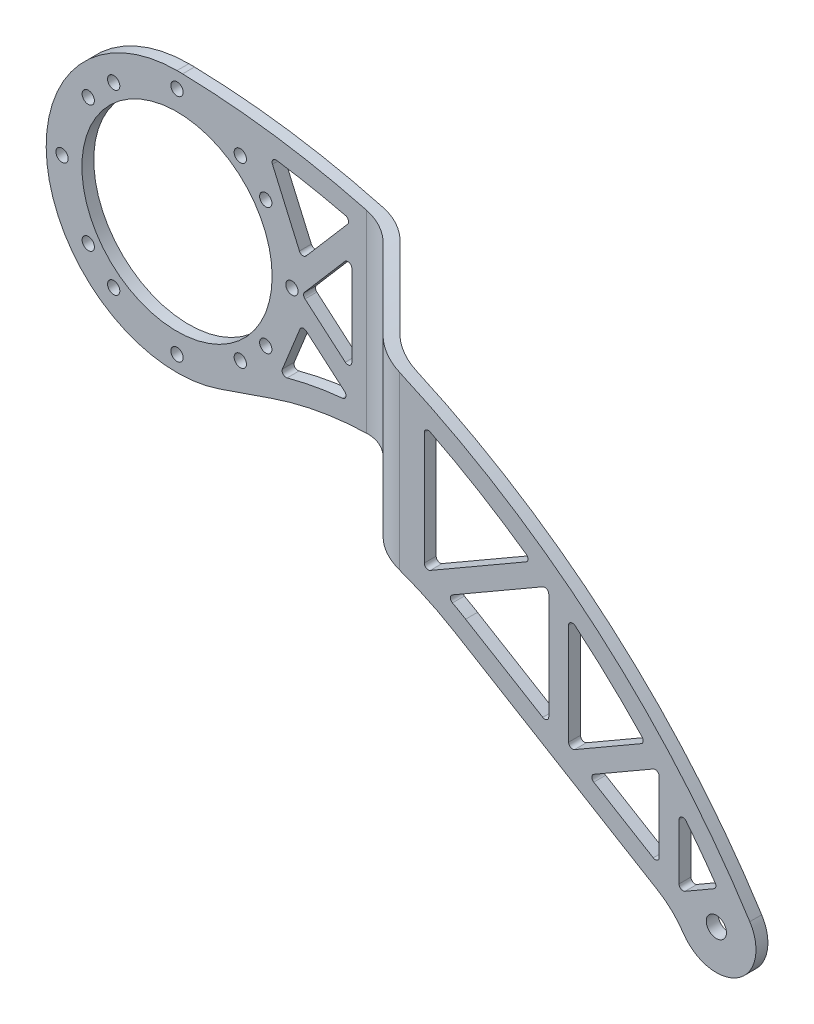
SolidWorks part; units mm, degrees
material "6061 合金"
ref_plane "前视基准面" through (0, 0, 0) normal (0, 0, 1) x (1, 0, 0)
ref_plane "上视基准面" through (0, 0, 0) normal (0, 1, 0) x (1, 0, 0)
ref_plane "右视基准面" through (0, 0, 0) normal (1, 0, 0) x (0, 0, -1)
other "Configuration Table"
sketch "草图1" plane through (0, 0, 0) normal (0, 0, 1) x (1, 0, 0)
  line L0 (-38.6665, 0) -> (31.2744, 0) construction
  line L1 (0, 22.4607) -> (0, -30.1372) construction
  line L4 (10.7304, -31.2067) -> (23.987, -26.6485)
  line L5 (91.2325, -33.7454) -> (142.3676, -64.5004)
  line L6 (157.0595, -65.0562) -> (0, 0) construction
  circle A7 centre (157.0595, -65.0562) radius 2.55
  arc A9 (0, 33) -> (10.7304, -31.2067) centre (0, 0) ccw
  arc A10 (148.7262, -70.5839) -> (165.4995, -59.6928) centre (157.0595, -65.0562) ccw
  arc A11 (1.4146, 32.9833) -> (165.4995, -59.6928) centre (-3.3007, -166.9611) cw
  arc A12 (23.987, -26.6485) -> (91.2325, -33.7454) centre (50, -102.3011) cw
  arc A13 (142.3676, -64.5004) -> (148.7262, -70.5839) centre (132.0595, -81.6393) cw
  arc A14 (1.4146, 32.9833) -> (0, 33) centre (0, -27) ccw
  dimension "D1" = 60
  dimension "D2" = 5.1
  dimension "D3" = 22.5
  dimension "D4" = 33
  dimension "D6" = 80
  dimension "D7" = 20
  dimension "D8" = 10
  dimension "D10" = 200
  dimension "D11" = 50
  dimension "D5" = 130
  dimension "D9" = 170
  dimension "D12" = 25
extrude "凸台-拉伸1" add sketch "草图1" along normal blind 3 and the other way blind 21
sketch "草图6" plane through (0, 0, 0) normal (0, 1, 0) x (1, 0, 0)
  line L0 (-33, 0) -> (47.8579, 0)
  line L2 (54.9289, 2.9289) -> (73, 21)
  line L3 (10.7304, 21) -> (-33, 21) construction
  line L5 (53.2426, -3) -> (71.3137, 15.0711)
  line L7 (78.3848, 18) -> (167.0595, 18)
  line L8 (167.0595, 18) -> (167.0595, -3)
  line L9 (167.0595, -3) -> (53.2426, -3)
  line L10 (73, 21) -> (-33, 21)
  line L12 (-33, 21) -> (-33, 0)
  line L13 (-33, 21) -> (-33, -3) construction
  line L14 (167.0595, -3) -> (167.0595, 21) construction
  line L15 (165.4995, 21) -> (1.4146, 21) construction
  line L16 (1.4146, -3) -> (165.4995, -3) construction
  arc A0 (71.3137, 15.0711) -> (78.3848, 18) centre (78.3848, 8) cw
  arc A1 (47.8579, 0) -> (54.9289, 2.9289) centre (47.8579, 10) ccw
  point P25 (52, 0)
  dimension "D5" = 10
  dimension "D1" = 3
  dimension "D2" = 3
  dimension "D3" = 45
  dimension "D4" = 85
extrude "切除-拉伸3" cut sketch "草图6" against normal through all both and the other way through all
sketch "草图2" plane through (0, 0, 3) normal (0, 0, 1) x (1, 0, 0)
  circle A0 centre (-29, 0) radius 1.55
  circle A2 centre (0, 0) radius 29 construction
  circle A3 centre (0, -29) radius 1.55
  circle A4 centre (0, 29) radius 1.55
  circle A5 centre (29, 0) radius 1.55
  dimension "D2" = 3.1
  dimension "D1" = 29
extrude "切除-拉伸1" cut sketch "草图2" against normal through all
sketch "草图4" plane through (0, 0, 3) normal (0, 0, 1) x (1, 0, 0)
  line L0 (35.2189, 0) -> (0, 0) construction
  line L1 (0, 0) -> (0, 39.685) construction
  line L2 (22.3882, 15.9693) -> (0, 0) construction
  line L3 (0, 0) -> (15.9693, 22.3882) construction
  line L4 (15.9693, -22.3882) -> (0, 0) construction
  line L5 (0, 0) -> (22.3882, -15.9693) construction
  line L6 (-22.3882, -15.9693) -> (0, 0) construction
  line L7 (0, 0) -> (-15.9693, -22.3882) construction
  line L8 (-15.9693, 22.3882) -> (0, 0) construction
  line L9 (0, 0) -> (-22.3882, 15.9693) construction
  circle A0 centre (0, 0) radius 27.5 construction
  circle A1 centre (-22.3882, 15.9693) radius 1.55
  circle A2 centre (15.9693, 22.3882) radius 1.55
  circle A3 centre (-15.9693, -22.3882) radius 1.55
  circle A4 centre (22.3882, -15.9693) radius 1.55
  circle A5 centre (-15.9693, 22.3882) radius 1.55
  circle A6 centre (22.3882, 15.9693) radius 1.55
  circle A7 centre (15.9693, -22.3882) radius 1.55
  circle A8 centre (-22.3882, -15.9693) radius 1.55
  point P16 (0, 0)
  dimension "D1" = 55
  dimension "D5" = 3.1
  dimension "D2" = 35.5
  dimension "D3" = 19
  dimension "D4" = 4
extrude "切除-拉伸2" cut sketch "草图4" against normal through all
fillet "圆角2" radius 10 2 edges at (73, -3.8831, -21) (53.2426, 1.2564, 3)
sketch "草图9" plane through (0, 0, -21) normal (0, 0, -1) x (-1, 0, 0)
  circle A0 centre (-157.0595, -65.0562) radius 7.75
  dimension "D1" = 15.5
sketch "草图10" plane through (0, 0, 3) normal (0, 0, 1) x (1, 0, 0)
  circle A0 centre (0, 0) radius 24
  dimension "D1" = 48
extrude "切除-拉伸5" cut sketch "草图10" against normal through all
sketch "草图12" plane through (0, 0, -18) normal (0, 0, 1) x (1, 0, 0)
  line L0 (83.3848, 6.0917) -> (83.3848, -22.3996)
  line L1 (84.8848, -23.2657) -> (109.0475, -9.3153)
  line L4 (93.8095, -29.4607) -> (144.9447, -60.2157)
  line L5 (83.3848, 7.7118) -> (83.3848, -24.1317)
  line L11 (113.2813, -12.6445) -> (90.4641, -25.818)
  line L12 (93.8095, -29.4607) -> (113.2659, -41.1626)
  line L13 (114.7813, -13.5105) -> (114.7813, -40.3057)
  line L14 (119.7813, -17.8314) -> (119.7813, -43.3492)
  line L15 (121.2813, -44.2152) -> (138.1188, -34.4941)
  line L16 (126.1486, -47.1786) -> (141.1555, -38.5143)
  line L17 (142.6555, -39.3804) -> (142.6555, -57.0705)
  line L18 (147.6555, -46.3571) -> (147.6555, -60.3684)
  line L19 (126.1332, -48.9016) -> (141.1401, -57.9274)
  line L20 (156.4448, -57.026) -> (149.1555, -61.2345)
  arc A0 (109.124, -7.6322) -> (84.8368, 6.9837) centre (-3.3007, -166.9611) ccw
  arc A1 (138.3452, -32.9408) -> (121.4209, -17.0627) centre (-3.3007, -166.9611) ccw
  arc A2 (161.2795, -62.3745) -> (83.3848, 7.7118) centre (-3.3007, -166.9611) ccw
  arc A4 (156.7656, -55.5888) -> (149.4388, -45.7354) centre (-3.3007, -166.9611) ccw
  arc A5 (149.4263, -63.6561) -> (144.9447, -60.2157) centre (132.0595, -81.6393) ccw construction
  arc A22 (152.8929, -67.82) -> (144.9447, -60.2157) centre (132.0595, -81.6393) ccw
  arc A24 (152.8929, -67.82) -> (161.2795, -62.3745) centre (157.0595, -65.0562) ccw
  arc A25 (147.6555, -46.3571) -> (149.4388, -45.7354) centre (148.6555, -46.3571) cw
  arc A26 (126.1486, -47.1786) -> (126.1332, -48.9016) centre (126.6486, -48.0446) ccw
  arc A27 (141.1555, -38.5143) -> (142.6555, -39.3804) centre (141.6555, -39.3804) cw
  arc A28 (138.1188, -34.4941) -> (138.3452, -32.9408) centre (137.6188, -33.628) ccw
  arc A29 (119.7813, -43.3492) -> (121.2813, -44.2152) centre (120.7813, -43.3492) ccw
  arc A30 (119.7813, -17.8314) -> (121.4209, -17.0627) centre (120.7813, -17.8314) cw
  arc A31 (114.7813, -40.3057) -> (113.2659, -41.1626) centre (113.7813, -40.3057) cw
  arc A32 (90.4641, -25.818) -> (90.4877, -27.5633) centre (90.9641, -26.684) ccw
  arc A33 (113.2813, -12.6445) -> (114.7813, -13.5105) centre (113.7813, -13.5105) cw
  arc A34 (109.0475, -9.3153) -> (109.124, -7.6322) centre (108.5475, -8.4493) ccw
  arc A35 (84.8848, -23.2657) -> (83.3848, -22.3996) centre (84.3848, -22.3996) cw
  arc A36 (84.8368, 6.9837) -> (83.3848, 6.0917) centre (84.3848, 6.0917) ccw
  arc A37 (142.6555, -57.0705) -> (141.1401, -57.9274) centre (141.6555, -57.0705) cw
  arc A38 (147.6555, -60.3684) -> (149.1555, -61.2345) centre (148.6555, -60.3684) ccw
  arc A39 (156.7656, -55.5888) -> (156.4448, -57.026) centre (155.9448, -56.16) cw
  arc A41 (93.8095, -29.4607) -> (83.3848, -24.1317) centre (50, -102.3011) ccw
  arc A42 (93.8095, -29.4607) -> (90.4877, -27.5633) centre (50, -102.3011) ccw
  point P5 (147.6555, -62.1005)
  point P19 (83.3848, -24.1317)
  point P30 (147.6555, -62.1005)
  point P35 (124.6791, -48.027)
  point P38 (142.6555, -37.6483)
  point P41 (139.212, -33.8629)
  point P44 (399.0304, 162.0422)
  point P45 (119.7813, -45.0813)
  point P54 (114.7813, -11.7784)
  point P57 (110.3955, -8.537)
  dimension "D6" = 60
  dimension "D9" = 5
  dimension "D2" = 5
  dimension "D11" = 60
  dimension "D12" = 1
  dimension "D13" = 1
  dimension "D7" = 1
  dimension "D3" = 5
  dimension "D4" = 60
  dimension "D5" = 60
  dimension "D8" = 5
  dimension "D1" = 5
extrude "切除-拉伸6" cut sketch "草图12" against normal through all
sketch "草图13" plane through (0, 0, 3) normal (0, 0, 1) x (1, 0, 0)
  line L0 (32.9388, 0) -> (0, 0) construction
  line L2 (24.0827, 24.5625) -> (30.8907, 9.0204)
  line L3 (32.565, 8.7697) -> (43.0399, 20.9561)
  line L4 (44.1005, -17.5061) -> (44.1005, 22.19)
  line L5 (9.1045, -26.4784) -> (22.3612, -21.9202)
  line L6 (44.1005, -8.7346) -> (44.1005, 11.822)
  line L8 (32.1804, 0.6518) -> (42.3422, 12.4738)
  line L9 (32.2869, -0.7584) -> (42.4487, -9.493)
  line L10 (32.5853, -7.6081) -> (42.2904, -15.9502)
  line L11 (31.0063, -7.9916) -> (26.5896, -18.9173)
  circle A0 centre (22.3882, -15.9693) radius 1.55 construction
  arc A1 (41.7358, -17.7038) -> (42.2904, -15.9502) centre (41.6386, -16.7085) ccw
  arc A2 (26.5896, -18.9173) -> (27.7781, -20.2573) centre (27.5167, -19.2921) ccw
  arc A3 (32.1804, 0.6518) -> (32.2869, -0.7584) centre (32.9388, 0) ccw
  arc A4 (32.5853, -7.6081) -> (31.0063, -7.9916) centre (31.9335, -8.3664) ccw
  arc A5 (42.4487, -9.493) -> (44.1005, -8.7346) centre (43.1005, -8.7346) ccw
  arc A6 (42.3422, 12.4738) -> (44.1005, 11.822) centre (43.1005, 11.822) cw
  arc A7 (30.8907, 9.0204) -> (32.565, 8.7697) centre (31.8066, 9.4216) ccw
  arc A8 (43.0399, 20.9561) -> (42.5165, 22.5799) centre (42.2815, 21.6079) ccw
  arc A9 (24.0827, 24.5625) -> (25.1446, 25.9531) centre (24.9987, 24.9638) cw
  circle A10 centre (22.3882, 15.9693) radius 1.55 construction
  arc A18 (44.1005, -17.5061) -> (22.3612, -21.9202) centre (50, -102.3011) ccw
  arc A19 (44.1005, 22.19) -> (1.2967, 27.9847) centre (-3.3007, -166.9611) ccw
  arc A20 (1.2967, 27.9847) -> (0, 28) centre (0, -27) ccw
  arc A21 (0, 28) -> (9.1045, -26.4784) centre (0, 0) ccw
  arc A22 (41.7358, -17.7038) -> (27.7781, -20.2573) centre (50, -102.3011) ccw
  arc A23 (42.5165, 22.5799) -> (25.1446, 25.9531) centre (-3.3007, -166.9611) ccw
  point P24 (31.5286, -0.1065)
  point P27 (31.5286, -6.6998)
  point P30 (44.1005, -10.9128)
  point P33 (44.1005, 14.5195)
  point P36 (31.5286, 7.564)
  dimension "D6" = 5
  dimension "D7" = 1
  dimension "D2" = 5
  dimension "D3" = 5
  dimension "D4" = 5
  dimension "D1" = 5
extrude "切除-拉伸7" cut sketch "草图13" against normal through all
mirror "镜向1" about plane through (132.0595, -81.6393, 3) normal (0, 0, -1) of bodies 115
delete or keep bodies "实体-删除/保留 1" type delete bodies bodies 115
